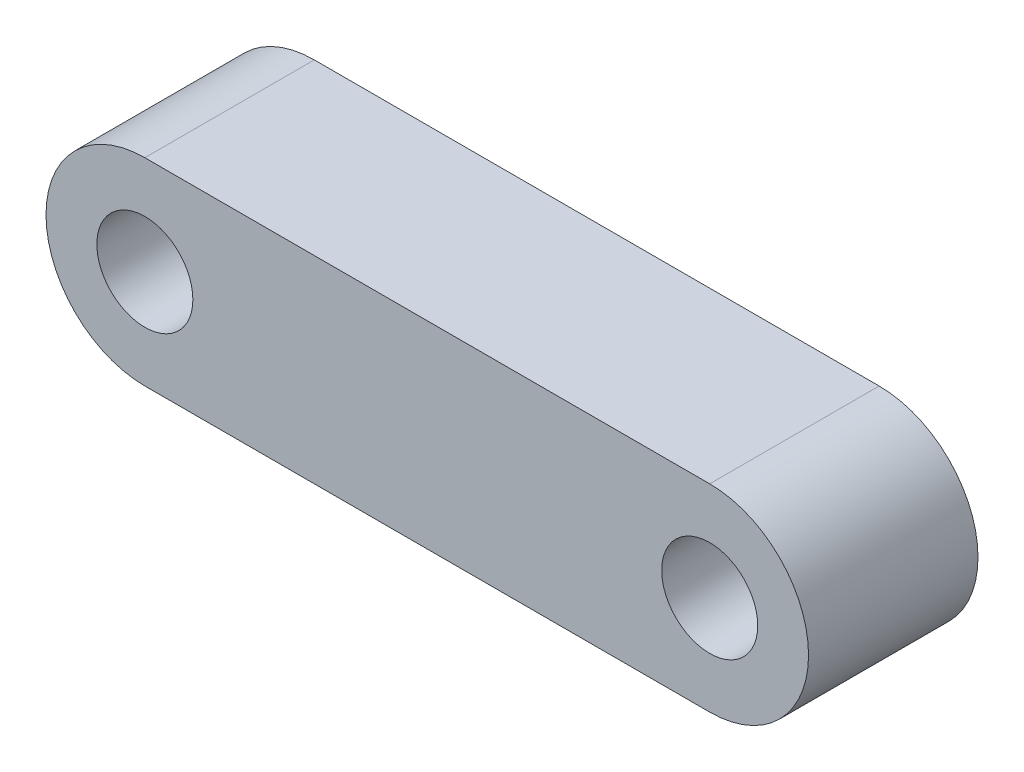
SolidWorks part; units mm, degrees
ref_plane "Plano frontal" through (0, 0, 0) normal (0, 0, 1) x (1, 0, 0)
ref_plane "Plano superior" through (0, 0, 0) normal (0, 1, 0) x (1, 0, 0)
ref_plane "Plano direito" through (0, 0, 0) normal (1, 0, 0) x (0, 0, -1)
sketch "Esboço1" plane through (0, 0, 0) normal (0, 0, 1) x (1, 0, 0)
  line L0 (10, 3.5) -> (-10, 3.5)
  line L1 (-10, -3.5) -> (10, -3.5)
  line L2 (-10, 0) -> (10, 0) construction
  arc A0 (-10, 3.5) -> (-10, -3.5) centre (-10, 0) ccw
  arc A1 (10, -3.5) -> (10, 3.5) centre (10, 0) ccw
  circle A2 centre (-10, 0) radius 1.7
  circle A3 centre (10, 0) radius 1.7
  point P8 (0, 0)
  point P11 (0, 0)
  dimension "D1" = 7
  dimension "D2" = 3.4
  dimension "D3" = 20
extrude "Ressalto-extrusão1" add sketch "Esboço1" along normal blind 6
sketch "Esboço2" plane through (0, 0, 0) normal (1, 0, 0) x (0, 0, -1)
  line L0 (0, 3.5) -> (-0.7, 3.1)
  line L1 (-0.7, 3.1) -> (-0.7, 2.9)
  line L2 (-0.7, 2.9) -> (0, 2.5)
  line L4 (0, 3.5) -> (0, 2.5)
  line L5 (0, -3.5) -> (0, 3.5) construction
  line L6 (0, 1.5) -> (-0.7, 1.1)
  line L7 (-0.7, 1.1) -> (-0.7, 0.9)
  line L8 (-0.7, 0.9) -> (0, 0.5)
  line L9 (0, 1.5) -> (0, 0.5)
  line L10 (0, -0.5) -> (-0.7, -0.9)
  line L11 (-0.7, -0.9) -> (-0.7, -1.1)
  line L12 (-0.7, -1.1) -> (0, -1.5)
  line L13 (0, -0.5) -> (0, -1.5)
  line L14 (0, -2.5) -> (-0.7, -2.9)
  line L15 (-0.7, -2.9) -> (-0.7, -3.1)
  line L16 (-0.7, -3.1) -> (0, -3.5)
  line L17 (0, -2.5) -> (0, -3.5)
  point P7 (0, 3)
  point P14 (-0.7, 3)
  dimension "D1" = 1
  dimension "D2" = 0.7
  dimension "D3" = 0.2
  dimension "D4" = 4
extrude "Corte-extrusão1" cut sketch "Esboço2" against normal mid plane 15
